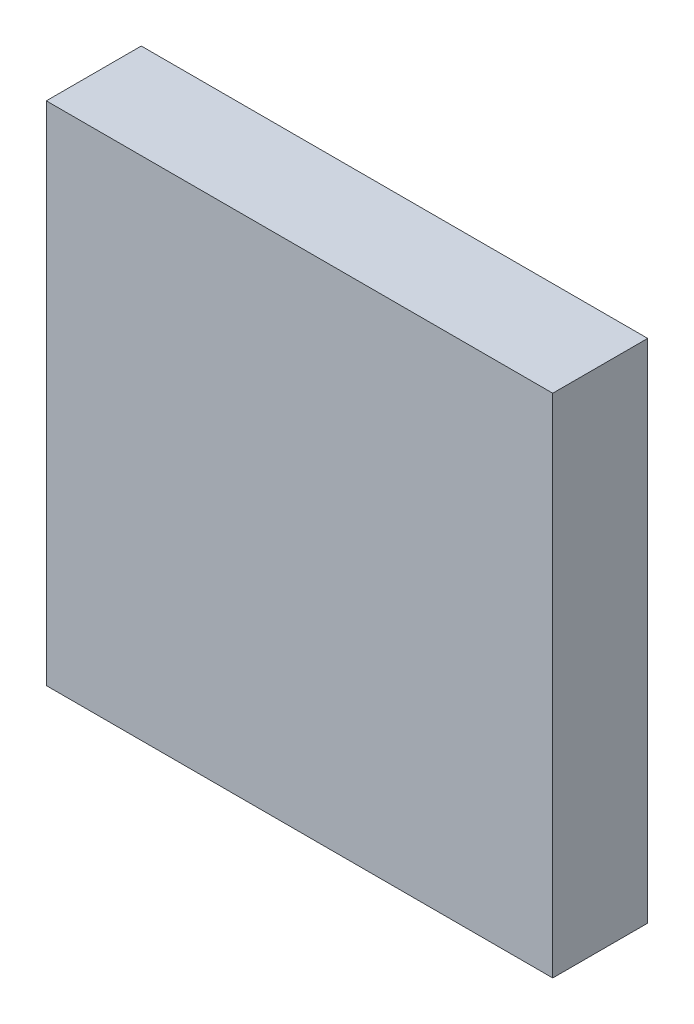
SolidWorks part; units mm, degrees
ref_plane "Front Plane" through (0, 0, 0) normal (0, 0, 1) x (1, 0, 0)
ref_plane "Top Plane" through (0, 0, 0) normal (0, 1, 0) x (1, 0, 0)
ref_plane "Right Plane" through (0, 0, 0) normal (1, 0, 0) x (0, 0, -1)
sketch "Sketch1" plane through (0, 0, 0) normal (0, 0, 1) x (1, 0, 0)
  line L1 (0, 0) -> (101.6, 0)
  line L2 (0, 0) -> (0, 101.6)
  line L3 (0, 101.6) -> (101.6, 101.6)
  line L4 (101.6, 0) -> (101.6, 101.6)
  dimension "D1" = 101.6
  dimension "D2" = 101.6
extrude "Boss-Extrude1" add sketch "Sketch1" along normal blind 19.05
sketch "Sketch2" plane through (0, 0, 19.05) normal (0, 0, 1) x (1, 0, 0)
  line L1 (12.7, 101.6) -> (12.7, 0)
  line L2 (101.6, 101.6) -> (0, 101.6) construction
  line L3 (0, 0) -> (101.6, 0) construction
  line L4 (0, 101.6) -> (0, 0) construction
  line L7 (38.1, 101.6) -> (38.1, 0)
  line L8 (63.5, 101.6) -> (63.5, 0)
  dimension "D1" = 12.7
  dimension "D2" = 3
sketch "Sketch3" plane through (0, 0, 0) normal (0, 0, -1) x (-1, 0, 0)
  line L1 (0, 12.7) -> (-102.2073, 12.7)
  line L2 (0, 101.6) -> (0, 0) construction
  line L3 (0, 0) -> (-101.6, 0) construction
  line L4 (0, 38.1) -> (-102.2073, 38.1)
  line L5 (0, 63.5) -> (-102.2073, 63.5)
  dimension "D1" = 12.7
  dimension "D2" = 3
